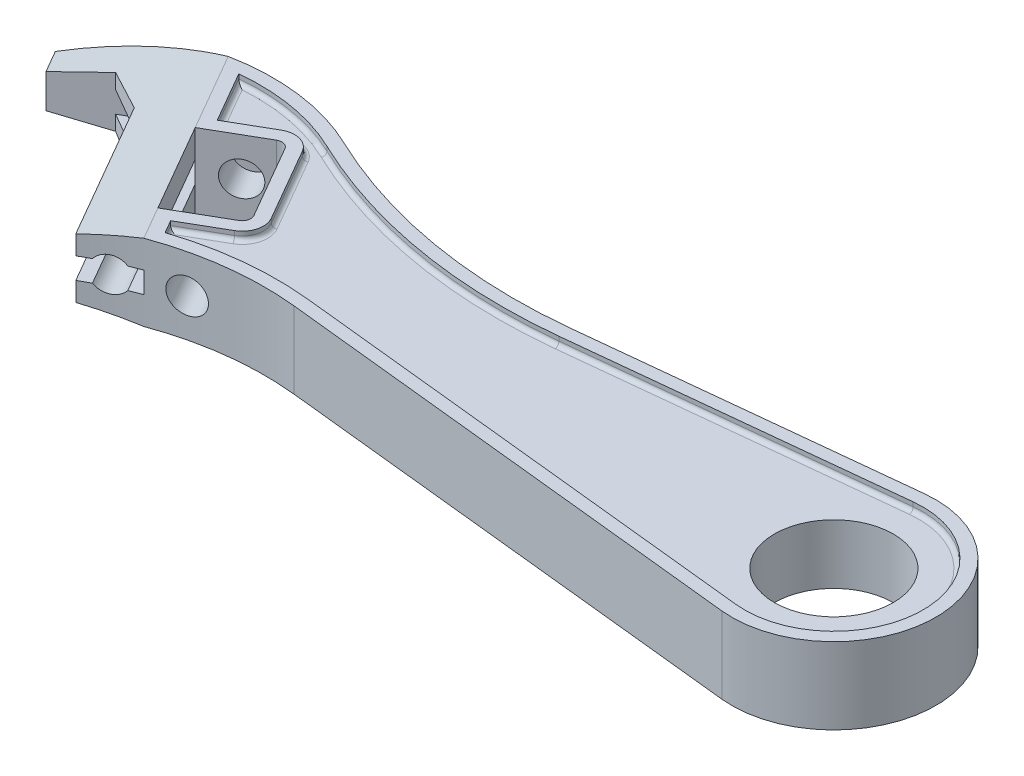
SolidWorks part; units mm, degrees
ref_plane "Front Plane" through (0, 0, 0) normal (0, 0, 1) x (1, 0, 0)
ref_plane "Top Plane" through (0, 0, 0) normal (0, 1, 0) x (1, 0, 0)
ref_plane "Right Plane" through (0, 0, 0) normal (1, 0, 0) x (0, 0, -1)
sketch "Sketch1" plane through (0, 0, 0) normal (0, 1, 0) x (1, 0, 0)
  line L0 (0, 0) -> (-99.0806, 0) construction
  line L1 (-1.2543, 11.9343) -> (-38.9855, 7.9686)
  line L2 (-57.5473, -6.0176) -> (-1.2543, -11.9343)
  line L3 (-100, 8.3677) -> (-98.5, 5.7696)
  line L4 (-98.5, 5.7696) -> (-93.3038, 8.7696)
  line L5 (-93.3038, 8.7696) -> (-88.1077, 5.7696)
  line L6 (-88.1077, 5.7696) -> (-78.7058, -10.515)
  line L7 (-81.5096, 6.3414) -> (-75.5096, -4.0509)
  line L8 (-75.5096, -4.0509) -> (-68.5814, -0.0509)
  line L9 (-68.5814, -0.0509) -> (-74.5814, 10.3414)
  line L10 (-74.5814, 10.3414) -> (-81.5096, 6.3414)
  arc A0 (-1.2543, -11.9343) -> (-1.2543, 11.9343) centre (0, 0) ccw
  circle A1 centre (0, 0) radius 7
  arc A3 (-38.9855, 7.9686) -> (-71.2058, 13.5411) centre (-45.2572, 67.6399) cw
  arc A4 (-71.2058, 13.5411) -> (-100, 8.3677) centre (-82.0177, -9) ccw
  arc A5 (-57.5473, -6.0176) -> (-78.7058, -10.515) centre (-61.2058, -40.8259) ccw
  arc A6 (-12, 0) -> (-1.2543, -11.9343) centre (0, 0) ccw construction
  arc A7 (-1.2543, 11.9343) -> (-12, 0) centre (0, 0) ccw construction
  point P17 (-67.6619, 2.9801)
  point P22 (-63.2376, -8.187)
  point P23 (-61.4151, -7.8485)
  point P24 (-64.4634, 10.6434)
  point P25 (-59.8744, 7.1228)
  point P26 (0, 0)
  dimension "D2" = 14
  dimension "D4" = 60
  dimension "D5" = 25
  dimension "D6" = 35
  dimension "D1" = 5
  dimension "D3" = 12
  dimension "D8" = 16
  dimension "D13" = 8
  dimension "D14" = 12
  dimension "D15" = 4
  dimension "D16" = 60
  dimension "D7" = 112
  dimension "D9" = 3
  dimension "D10" = 6
  dimension "D11" = 6
  dimension "D12" = 30
  dimension "D17" = 8
  dimension "D18" = 15
extrude "Boss-Extrude1" add sketch "Sketch1" along normal mid plane 9
sketch "Sketch2" plane through (-23.1233, 0, -40.0507) normal (0.5, 0, 0.866) x (0.866, 0, -0.5)
  line L0 (0, 0) -> (-105.4348, 0) construction
  line L1 (-82.4187, 4.5) -> (-82.4187, -4.5) construction
  circle A0 centre (-63.4187, 0) radius 2
  point P5 (0, 0)
  dimension "D1" = 4
  dimension "D2" = 19
extrude "Cut-Extrude1" cut sketch "Sketch2" against normal blind 4 and the other way through all
sketch "Sketch3" plane through (-27.1233, 0, -46.9789) normal (0.5, 0, 0.866) x (0.866, 0, -0.5)
  line L0 (0, 0) -> (-67.4187, 0) construction
  line L1 (-82.4187, 4.5) -> (-82.4187, -4.5) construction
  line L2 (-71.98, 1.25) -> (-68.8575, 1.25) construction
  line L3 (-82.4187, -1.25) -> (-71.98, -1.25)
  line L4 (-82.4187, -1.25) -> (-82.4187, 1.25)
  line L5 (-82.4187, 1.25) -> (-71.98, 1.25)
  line L6 (-67.4187, -1.25) -> (-67.4187, 1.25)
  line L7 (-68.8575, 1.25) -> (-67.4187, 1.25)
  line L8 (-67.4187, 0) -> (-68.4187, 0) construction
  line L9 (-68.4187, 0) -> (-145.3141, 0) construction
  line L10 (-71.98, -1.25) -> (-68.8575, -1.25) construction
  line L11 (-68.8575, -1.25) -> (-67.4187, -1.25)
  arc A0 (-71.98, -1.25) -> (-68.8575, -1.25) centre (-70.4187, 0) ccw
  arc A1 (-71.98, 1.25) -> (-72.4187, 0) centre (-70.4187, 0) ccw construction
  arc A2 (-68.4187, 0) -> (-68.8575, 1.25) centre (-70.4187, 0) ccw construction
  arc A3 (-68.8575, 1.25) -> (-71.98, 1.25) centre (-70.4187, 0) ccw
  arc A4 (-72.4187, 0) -> (-71.98, -1.25) centre (-70.4187, 0) ccw construction
  arc A5 (-68.8575, -1.25) -> (-68.4187, 0) centre (-70.4187, 0) ccw construction
  point P17 (-62.4053, 0.9714)
  dimension "D1" = 4
  dimension "D2" = 12
  dimension "D3" = 2.5
  dimension "D4" = 15
extrude "Cut-Extrude2" cut sketch "Sketch3" along normal through all
sketch "Sketch4" plane through (-27.1233, 0, -46.9789) normal (0.5, 0, 0.866) x (0.866, 0, -0.5)
  line L0 (-82.4187, 4.5) -> (-82.4187, 2)
  line L1 (-82.4187, 4.5) -> (-82.4187, -4.5) construction
  line L2 (-82.4187, 2) -> (-67.4187, 4.5)
  line L3 (-52.8462, 4.5) -> (-73.4187, 4.5) construction
  line L4 (-67.4187, 4.5) -> (-82.4187, 4.5)
  line L5 (0, 0) -> (-102.8552, 0) construction
  line L6 (-82.4187, -4.5) -> (-82.4187, -2)
  line L7 (-82.4187, -2) -> (-67.4187, -4.5)
  line L8 (-67.4187, -4.5) -> (-82.4187, -4.5)
  dimension "D1" = 15
  dimension "D2" = 2.5
extrude "Cut-Extrude3" cut sketch "Sketch4" against normal through all both and the other way through all
fillet "Fillet1" radius 1 2 edges at (-68.5814, 0, 0.0509) (-74.5814, 0, -10.3414)
sketch "Sketch5" plane through (0, 4.5, 0) normal (0, 1, 0) x (1, 0, 0)
  line L21 (-84.417, 14.3772) -> (-80.9606, 8.3904)
  line L22 (-80.9606, 8.3904) -> (-76.1974, 11.1404)
  line L23 (-72.7824, 10.2254) -> (-67.7824, 1.5651)
  line L24 (-68.6974, -1.85) -> (-73.4606, -4.6)
  line L25 (-73.4606, -4.6) -> (-72.5712, -6.1405)
  line L26 (-57.3905, -4.5259) -> (-1.0975, -10.4425)
  line L27 (-1.0975, 10.4425) -> (-38.8287, 6.4768)
  line L28 (-84.417, 14.3772) -> (-80.9606, 8.3904)
  line L29 (-80.9606, 8.3904) -> (-76.1974, 11.1404)
  line L30 (-72.7824, 10.2254) -> (-67.7824, 1.5651)
  line L31 (-68.6974, -1.85) -> (-73.4606, -4.6)
  line L32 (-73.4606, -4.6) -> (-72.5712, -6.1405)
  line L33 (-57.3905, -4.5259) -> (-1.0975, -10.4425)
  line L34 (-1.0975, 10.4425) -> (-38.8287, 6.4768)
  arc A18 (-71.8545, 12.1887) -> (-84.417, 14.3772) centre (-82.0177, -9) ccw
  arc A19 (-72.7824, 10.2254) -> (-76.1974, 11.1404) centre (-74.9474, 8.9754) ccw
  arc A20 (-68.6974, -1.85) -> (-67.7824, 1.5651) centre (-69.9474, 0.3151) ccw
  arc A21 (-57.3905, -4.5259) -> (-72.5712, -6.1405) centre (-61.2058, -40.8259) ccw
  arc A22 (-1.0975, -10.4425) -> (-1.0975, 10.4425) centre (0, 0) ccw
  arc A23 (-71.8545, 12.1887) -> (-38.8287, 6.4768) centre (-45.2572, 67.6399) ccw
  arc A24 (-71.8545, 12.1887) -> (-84.417, 14.3772) centre (-82.0177, -9) ccw
  arc A25 (-72.7824, 10.2254) -> (-76.1974, 11.1404) centre (-74.9474, 8.9754) ccw
  arc A26 (-68.6974, -1.85) -> (-67.7824, 1.5651) centre (-69.9474, 0.3151) ccw
  arc A27 (-57.3905, -4.5259) -> (-72.5712, -6.1405) centre (-61.2058, -40.8259) ccw
  arc A28 (-1.0975, -10.4425) -> (-1.0975, 10.4425) centre (0, 0) ccw
  arc A29 (-71.8545, 12.1887) -> (-38.8287, 6.4768) centre (-45.2572, 67.6399) ccw
  dimension "D1" = 1.5
extrude "Cut-Extrude4" cut sketch "Sketch5" against normal blind 1 and the other way through all
fillet "Fillet2" radius 0.5 13 edges at (-78.579, 3.5, -9.7654) (-74.3004, 3.5, -11.3902) (-71.079, 3.5, 3.225) (-67.5326, 3.5, 0.3319) (-65.0662, 3.5, 4.5306) (-29.244, 3.5, 7.4842) (10.5, 3.5, 0) (-19.9631, 3.5, -8.4596) (-55.7382, 3.5, -7.0395) (-73.0159, 3.5, 5.3702) (-70.2824, 3.5, -5.8952) (-82.6888, 3.5, -11.3838) (-77.9845, 3.5, -14.1513)
mirror "Mirror1" about plane through (0, 0, 0) normal (0, 1, 0) of "Cut-Extrude4", "Fillet2"
equation "\"A\"= 112"
equation "\"D7@Sketch1\"=\"A\""
